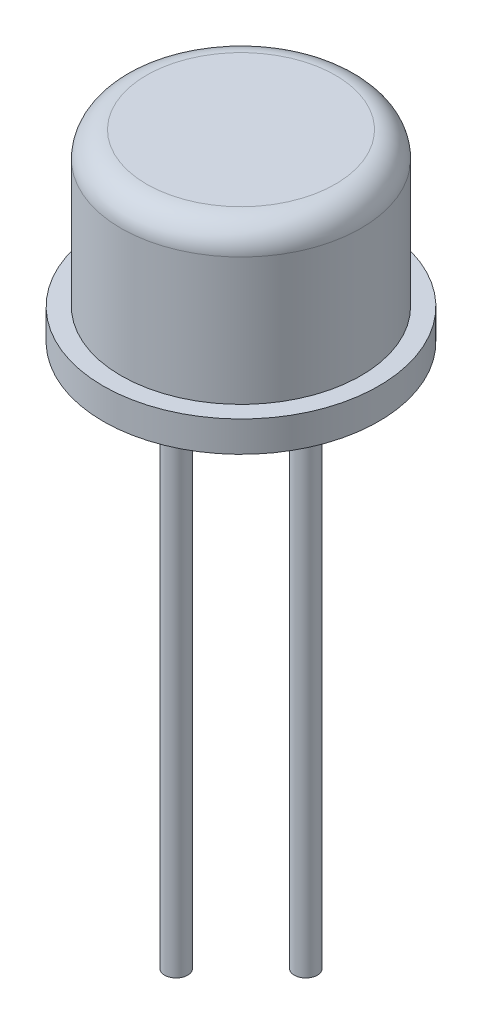
SolidWorks part; units mm, degrees
ref_plane "Спереди" through (0, 0, 0) normal (0, 0, 1) x (1, 0, 0)
ref_plane "Сверху" through (0, 0, 0) normal (0, 1, 0) x (1, 0, 0)
ref_plane "Справа" through (0, 0, 0) normal (1, 0, 0) x (0, 0, -1)
sketch "Эскиз1" plane through (0, 0, 0) normal (0, 1, 0) x (1, 0, 0)
  circle A0 centre (0, 0) radius 2.7
extrude "Бобышка-Вытянуть1" add sketch "Эскиз1" along normal blind 0.6
sketch3d "Трехмерный эскиз1"
  line L1 (0, 0.6, 0) -> (-2.35, 0.6, 0)
  line L2 (-2.35, 0.6, 0) -> (-2.35, 3.1, 0)
  line L3 (-1.85, 3.6, 0) -> (0, 3.6, 0)
  line L6 (0, 7.9369, 0) -> (0, -0.7369, 0) construction
  line L7 (0, 3.6, 0) -> (0, 0.6, 0)
  arc A0 (-2.35, 3.1, 0) -> (-1.85, 3.6, 0) centre (-1.85, 3.1, 0) ccw
  point P7 (-2.35, 3.6, 0)
  point P8 (-1.85, 3.1, -0.5)
  point P10 (0, 3.6, 0)
  point P11 (0, 3.6, 0)
  dimension "D1" = 0.5
  dimension "D2" = 2.5
  dimension "D3" = 3
  dimension "D4" = 2.35
revolve "Повернуть1" add sketch "Трехмерный эскиз1" angle 360 about L6
sketch "Эскиз5" plane through (0, 0, 0) normal (0, -1, 0) x (1, 0, 0)
  circle A1 centre (1.27, 0) radius 0.225
  circle A2 centre (0, 1.27) radius 0.225
  circle A3 centre (0, -1.27) radius 0.225
extrude "Бобышка-Вытянуть2" add sketch "Эскиз5" along normal blind 10
